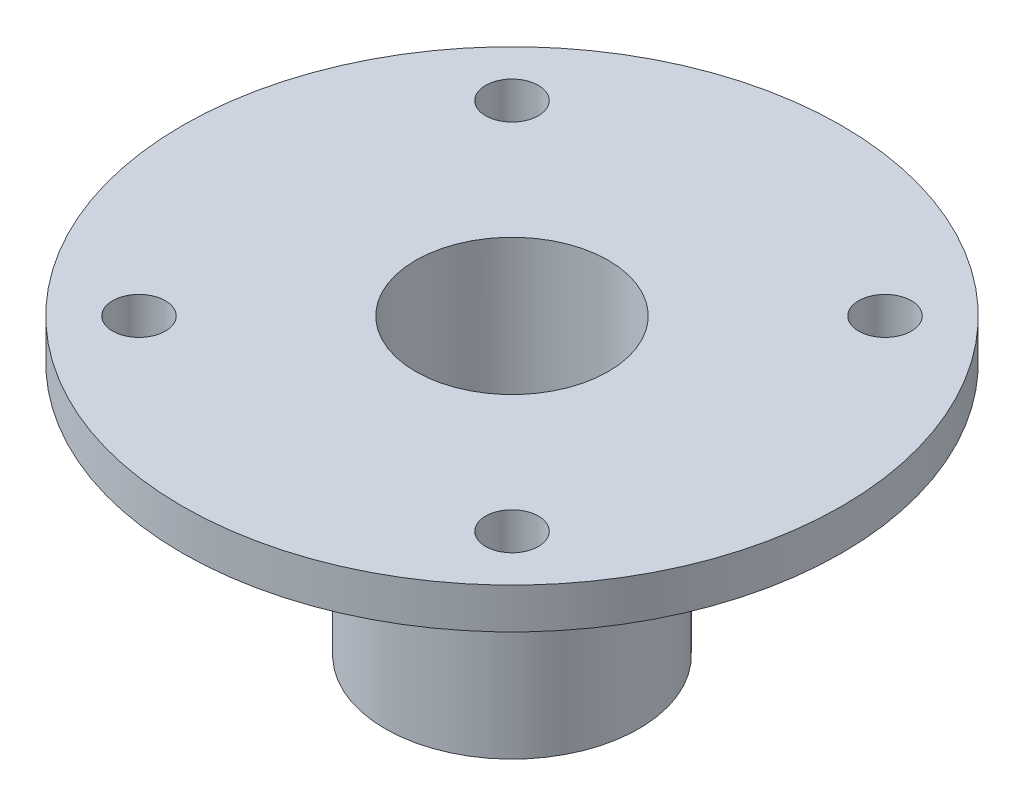
SolidWorks part; units mm, degrees
ref_plane "Front Plane" through (0, 0, 0) normal (0, 0, 1) x (1, 0, 0)
ref_plane "Top Plane" through (0, 0, 0) normal (0, 1, 0) x (1, 0, 0)
ref_plane "Right Plane" through (0, 0, 0) normal (1, 0, 0) x (0, 0, -1)
sketch "Sketch1" plane through (0, 0, 0) normal (0, 1, 0) x (1, 0, 0)
  line L1 (18.3848, -18.3848) -> (-18.3848, -18.3848) construction
  line L2 (18.3848, -18.3848) -> (18.3848, 18.3848) construction
  line L3 (18.3848, 18.3848) -> (-18.3848, 18.3848) construction
  line L4 (-18.3848, -18.3848) -> (-18.3848, 18.3848) construction
  line L5 (18.3848, -18.3848) -> (-18.3848, 18.3848) construction
  line L6 (18.3848, 18.3848) -> (-18.3848, -18.3848) construction
  circle A0 centre (0, 0) radius 9.5
  circle A1 centre (0, 0) radius 26 construction
  circle A2 centre (18.3848, -18.3848) radius 2.6
  circle A3 centre (-18.3848, -18.3848) radius 2.6
  circle A4 centre (-18.3848, 18.3848) radius 2.6
  circle A5 centre (18.3848, 18.3848) radius 2.6
  circle A6 centre (0, 0) radius 32.5
  dimension "D1" = 19
  dimension "D2" = 52
  dimension "D4" = 5.2
  dimension "D5" = 65
extrude "Boss-Extrude1" add sketch "Sketch1" along normal blind 4
sketch "Sketch2" plane through (0, 0, 0) normal (0, -1, 0) x (1, 0, 0)
  circle A0 centre (0, 0) radius 12.5
  circle A4 centre (0, 0) radius 9.5 construction
  circle A5 centre (0, 0) radius 9.5
  dimension "D1" = 25
extrude "Boss-Extrude2" add sketch "Sketch2" along normal blind 17
sketch "Sketch3" plane through (0, -17, 0) normal (0, -1, 0) x (1, 0, 0)
  circle A1 centre (0, 0) radius 12.5
  circle A2 centre (0, 0) radius 12.5
  dimension "D1" = 0
extrude "Boss-Extrude3" add sketch "Sketch3" along normal blind 8
sketch "Sketch4" plane through (0, -25, 0) normal (0, -1, 0) x (1, 0, 0)
  circle A0 centre (0, 0) radius 3.1
  dimension "D1" = 6.2
extrude "Cut-Extrude3" cut sketch "Sketch4" against normal up to next
fillet "Fillet1" radius 2 1 edges at (0, 0, 12.5)
